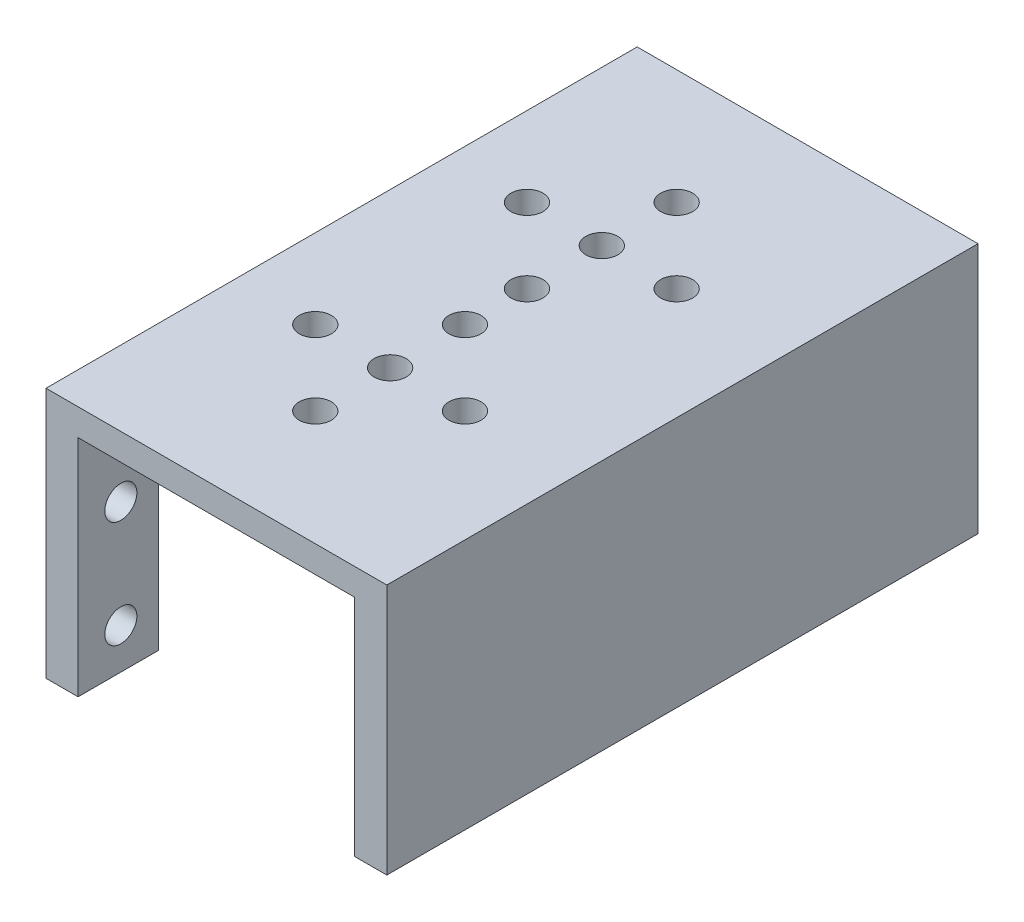
SolidWorks part; units mm, degrees
ref_plane "Alzado" through (0, 0, 0) normal (0, 0, 1) x (1, 0, 0)
ref_plane "Planta" through (0, 0, 0) normal (0, 1, 0) x (1, 0, 0)
ref_plane "Vista lateral" through (0, 0, 0) normal (1, 0, 0) x (0, 0, -1)
sketch "Croquis1" plane through (0, 0, 0) normal (0, 1, 0) x (1, 0, 0)
  line L0 (0, 0) -> (0, 55.3)
  line L1 (0, 55.3) -> (28.88, 55.3)
  line L2 (28.88, 55.3) -> (28.88, 0)
  line L3 (28.88, 0) -> (0, 0)
  line L4 (14.44, 0) -> (14.44, 17.75) construction
  line L5 (0, 27.65) -> (28.88, 27.65) construction
  line L6 (14.44, 0) -> (12.74, 0) construction
  circle A18 centre (14.44, 17.75) radius 1.5
  circle A19 centre (21.44, 17.75) radius 1.5
  circle A20 centre (14.44, 24.75) radius 1.5
  circle A21 centre (7.44, 17.75) radius 1.5
  circle A22 centre (14.44, 10.75) radius 1.5
  circle A23 centre (21.44, 37.55) radius 1.5
  circle A24 centre (14.44, 44.55) radius 1.5
  circle A25 centre (14.44, 30.55) radius 1.5
  circle A26 centre (14.44, 37.55) radius 1.5
  circle A27 centre (7.44, 37.55) radius 1.5
  dimension "D3" = 17.75
  dimension "D4" = 7
  dimension "D1" = 28.88
  dimension "D2" = 55.3
  dimension "D5" = 7
  dimension "D6" = 7
  dimension "D7" = 7
extrude "Saliente-Extruir8" add sketch "Croquis1" along normal blind 3
sketch "Croquis19" plane through (0, 3, 0) normal (0, 1, 0) x (1, 0, 0)
  line L1 (0, 55.3) -> (28.88, 55.3)
  line L2 (0, 55.3) -> (0, 0)
  line L3 (0, 0) -> (28.88, 0)
  line L4 (28.88, 55.3) -> (28.88, 0)
extrude "Cortar-Extruir3" cut sketch "Croquis19" against normal blind 0.5
sketch "Croquis20" plane through (0, 2.5, 0) normal (0, 1, 0) x (1, 0, 0)
  line L0 (0, 27.65) -> (28.88, 27.65) construction
  line L1 (0, 55.3) -> (3, 55.3)
  line L2 (0, 55.3) -> (0, 47.8)
  line L3 (0, 47.8) -> (3, 47.8)
  line L4 (3, 55.3) -> (3, 47.8)
  line L5 (0, 55.3) -> (0, 0) construction
  line L6 (28.88, 0) -> (28.88, 55.3) construction
  line L7 (0, 7.5) -> (3, 7.5)
  line L8 (3, 0) -> (3, 7.5)
  line L9 (0, 0) -> (3, 0)
  line L10 (0, 0) -> (0, 7.5)
  dimension "D1" = 3
  dimension "D2" = 7.5
extrude "Saliente-Extruir18" add sketch "Croquis20" along normal blind 23.5
sketch "Croquis21" plane through (0, 26, 0) normal (0, 1, 0) x (1, 0, 0)
  line L1 (0, 55.3) -> (28.88, 55.3)
  line L2 (0, 55.3) -> (0, 0)
  line L3 (0, 0) -> (28.88, 0)
  line L4 (28.88, 55.3) -> (28.88, 0)
  circle A0 centre (14.44, 44.55) radius 1.5
  circle A1 centre (21.44, 37.55) radius 1.5
  circle A2 centre (14.44, 37.55) radius 1.5
  circle A3 centre (14.44, 30.55) radius 1.5
  circle A4 centre (7.44, 37.55) radius 1.5
  circle A5 centre (14.44, 24.75) radius 1.5
  circle A6 centre (21.44, 17.75) radius 1.5
  circle A7 centre (14.44, 17.75) radius 1.5
  circle A8 centre (7.44, 17.75) radius 1.5
  circle A9 centre (14.44, 10.75) radius 1.5
extrude "Saliente-Extruir19" add sketch "Croquis21" against normal blind 2.5
sketch "Croquis22" plane through (0, 0, 0) normal (-1, 0, 0) x (0, 0, 1)
  line L0 (-55.3, 13) -> (-55.3, 11.3) construction
  line L1 (-55.3, 26) -> (-55.3, 0) construction
  line L2 (-55.3, 13) -> (0, 13) construction
  line L3 (0, 26) -> (0, 0) construction
  line L4 (-55.3, 11.3) -> (-51.3, 11.3) construction
  line L5 (-51.3, 11.3) -> (-51.3, 6.3) construction
  line L6 (-51.3, 11.3) -> (-51.3, 16.3) construction
  line L7 (-27.65, 0) -> (-27.65, 26) construction
  line L8 (-55.3, 0) -> (0, 0) construction
  line L9 (-55.3, 26) -> (0, 26) construction
  line L10 (-47.8, 23.5) -> (-47.8, 2.5) construction
  circle A0 centre (-51.3, 6.3) radius 1.5
  circle A1 centre (-51.3, 16.3) radius 1.5
  circle A2 centre (-4, 16.3) radius 1.5
  circle A3 centre (-4, 6.3) radius 1.5
  dimension "D4" = 5
  dimension "D1" = 1.7
  dimension "D2" = 3.5
  dimension "D3" = 5
extrude "Cortar-Extruir4" cut sketch "Croquis22" against normal blind 3
sketch "Croquis23" plane through (0, 0, 0) normal (-1, 0, 0) x (0, 0, 1)
  line L1 (-55.3, 0) -> (0, 0)
  line L2 (-55.3, 0) -> (-55.3, 2.5)
  line L3 (-55.3, 2.5) -> (0, 2.5)
  line L4 (0, 0) -> (0, 2.5)
extrude "Cortar-Extruir5" cut sketch "Croquis23" against normal through all
sketch "Croquis24" plane through (28.88, 0, 0) normal (1, 0, 0) x (0, 0, -1)
  line L1 (0, 26) -> (55.3, 26)
  line L2 (0, 26) -> (0, 2.5)
  line L3 (0, 2.5) -> (55.3, 2.5)
  line L4 (55.3, 26) -> (55.3, 2.5)
extrude "Saliente-Extruir20" add sketch "Croquis24" along normal blind 3
